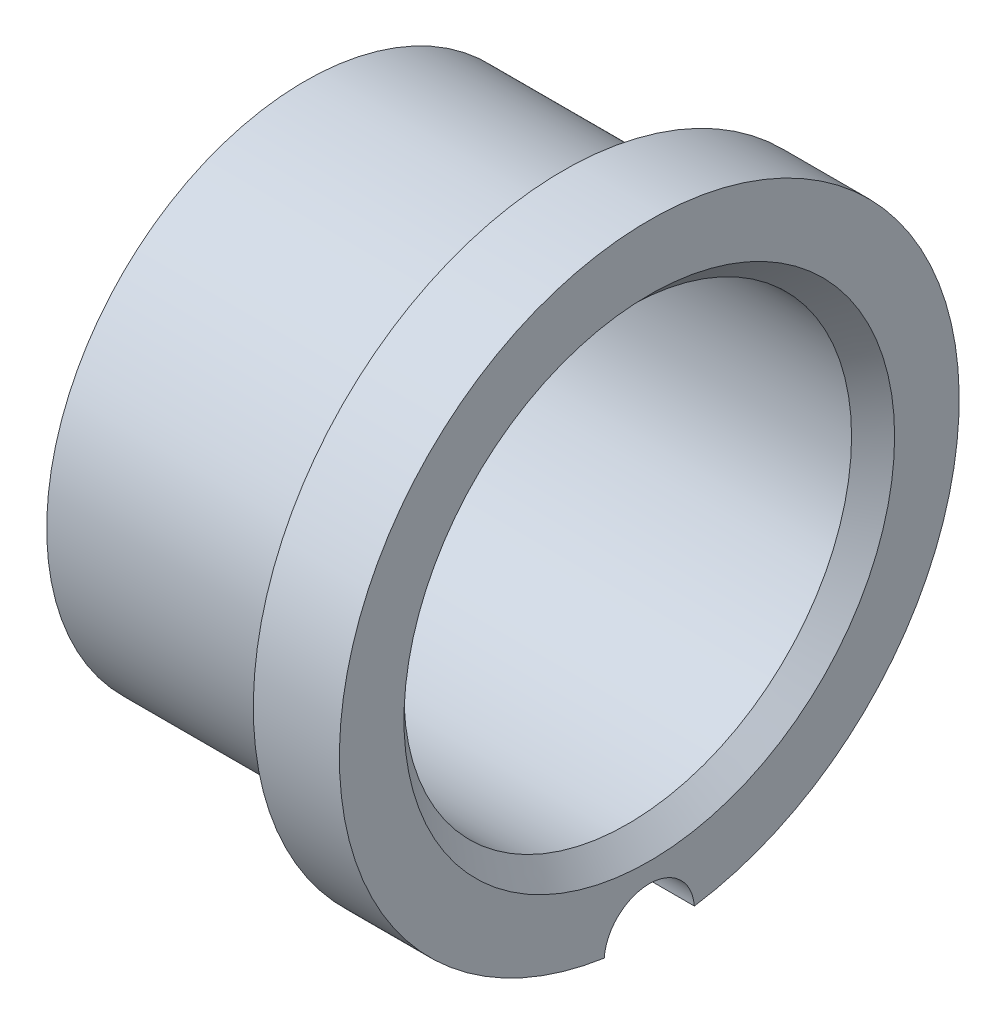
SolidWorks part; units mm, degrees
ref_plane "Front Plane" through (0, 0, 0) normal (0, 0, 1) x (1, 0, 0)
ref_plane "Top Plane" through (0, 0, 0) normal (0, 1, 0) x (1, 0, 0)
ref_plane "Right Plane" through (0, 0, 0) normal (1, 0, 0) x (0, 0, -1)
sketch "Sketch2" plane through (0, 0, 0) normal (1, 0, 0) x (0, 0, -1)
  circle A0 centre (0, 0) radius 30
extrude "Boss-Extrude1" add sketch "Sketch2" along normal blind 30 contours A0
sketch "Sketch3" plane through (30, 0, 0) normal (1, 0, 0) x (0, 0, -1)
  circle A0 centre (0, 0) radius 36
extrude "Boss-Extrude2" add sketch "Sketch3" along normal blind 10
sketch "Sketch4" plane through (40, 0, 0) normal (1, 0, 0) x (0, 0, -1)
  circle A0 centre (0, 0) radius 26
extrude "Cut-Extrude1" cut sketch "Sketch4" against normal through all
chamfer "Chamfer1" distance 2.5 1 edges at (40, 0, -26)
sketch "Esquisse1" plane through (40, 0, 0) normal (1, 0, 0) x (0, 0, -1)
  line L0 (0, 0) -> (0, -36) construction
  circle A0 centre (0, 0) radius 36 construction
  point P1 (0, -36)
  point P10 (0, -36)
  dimension "D1" = 0
hole_wizard "Dégagement M101" positions "Esquisse1" profile "Esquisse2" hole size "M10" standard "Ansi Metric"
sketch "Esquisse2" plane through (40, -36, 0) normal (0, 1, 0) x (0, 0, -1)
  line L0 (0, 0) -> (0, 23.1545)
  line L1 (0, 23.1545) -> (5.25, 20)
  line L2 (5.25, 20) -> (5.25, 0)
  line L5 (5.25, 0) -> (0, 0)
  line L10 (0, 23.1545) -> (-5.25, 20) construction
  line L11 (0, -6.35) -> (0, 107.95) construction
  dimension "Diamètre du perçage" = 10.5
  dimension "Profondeur du perçage" = 20
  dimension "Angle de pointe" = 118
